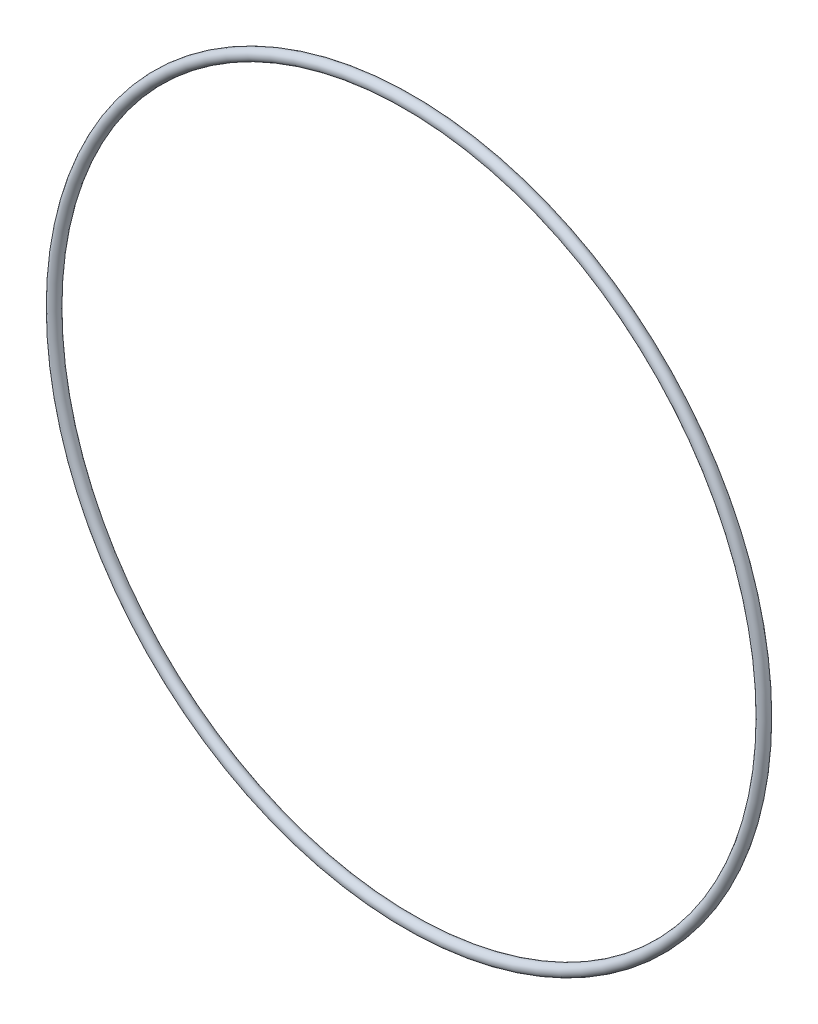
SolidWorks part; units mm, degrees
ref_plane "Front" through (0, 0, 0) normal (0, 0, 1) x (1, 0, 0)
ref_plane "Top" through (0, 0, 0) normal (0, 1, 0) x (1, 0, 0)
ref_plane "Right" through (0, 0, 0) normal (1, 0, 0) x (0, 0, -1)
sketch "Sketch1" plane through (0, 0, 0) normal (1, 0, 0) x (0, -1, 0)
  line L0 (0, -1.3081) -> (0, 1.3081) construction
  line L2 (-93.5012, 0) -> (93.5012, 0) construction
  line L3 (-82.3849, 0) -> (82.3849, 0) construction
  circle A0 centre (83.693, 0) radius 1.3081
  point P9 (82.3849, 0)
  point P10 (85.0011, 0)
  point P13 (83.693, 1.3081)
  point P14 (83.693, -1.3081)
  dimension "Width" = 2.6162
  dimension "ID" = 164.7698
revolve "Revolve1" add sketch "Sketch1" angle 360 about L0
